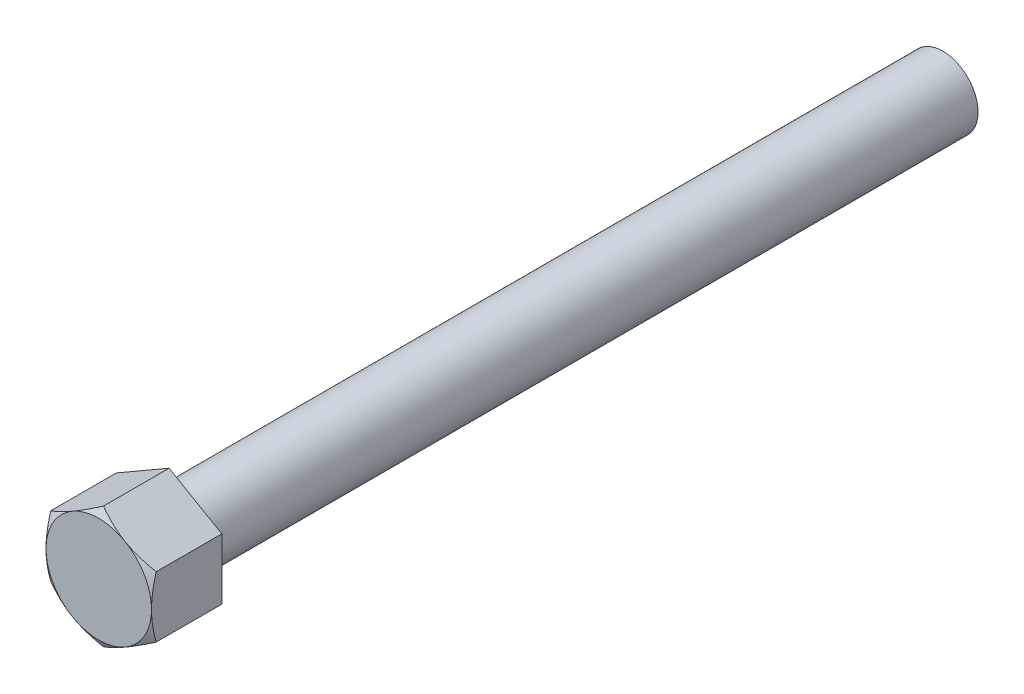
SolidWorks part; units mm, degrees
material "Copper"
ref_plane "Front Plane" through (0, 0, 0) normal (0, 0, 1) x (1, 0, 0)
ref_plane "Top Plane" through (0, 0, 0) normal (0, 1, 0) x (1, 0, 0)
ref_plane "Right Plane" through (0, 0, 0) normal (1, 0, 0) x (0, 0, -1)
sketch "Sketch1" plane through (0, 0, 0) normal (0, 0, 1) x (1, 0, 0)
  line L1 (0, 17.3205) -> (-15, 8.6603)
  line L2 (-15, 8.6603) -> (-15, -8.6603)
  line L3 (-15, -8.6603) -> (0, -17.3205)
  line L4 (0, -17.3205) -> (15, -8.6603)
  line L5 (15, -8.6603) -> (15, 8.6603)
  line L6 (15, 8.6603) -> (0, 17.3205)
  circle A0 centre (0, 0) radius 15 construction
  dimension "D1" = 30
extrude "Boss-Extrude1" add sketch "Sketch1" along normal blind 20
sketch "Sketch2" plane through (0, 0, 20) normal (0, 0, 1) x (1, 0, 0)
  circle A0 centre (0, 0) radius 15
  dimension "D1" = 30
extrude "Cut-Extrude1" cut sketch "Sketch2" against normal blind 5 draft 60 flip side to cut
sketch "Sketch3" plane through (0, 0, 0) normal (0, 0, -1) x (-1, 0, 0)
  circle A0 centre (0, 0) radius 10
  dimension "D1" = 20
extrude "Boss-Extrude2" add sketch "Sketch3" along normal blind 220
sketch "Sketch44" plane through (0, 0, -220) normal (0, 0, -1) x (-1, 0, 0)
  circle A0 centre (0, 0) radius 10
